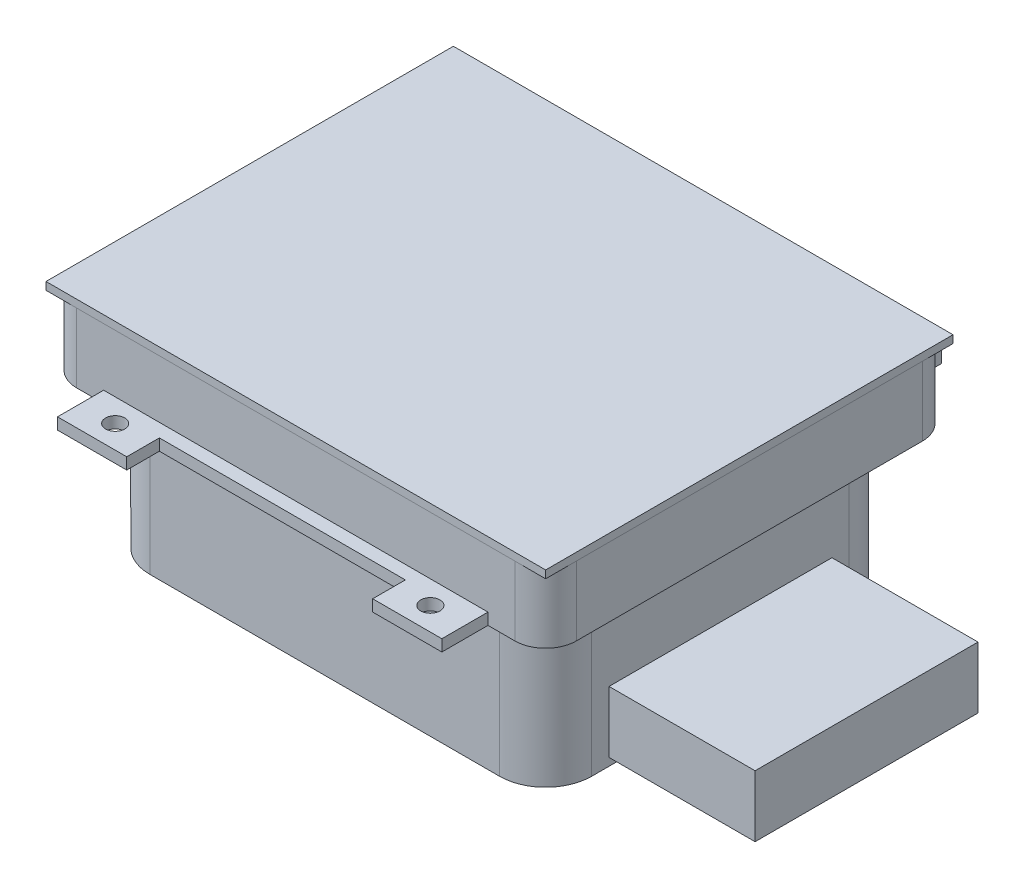
SolidWorks part; units mm, degrees
ref_plane "前视基准面" through (0, 0, 0) normal (0, 0, 1) x (1, 0, 0)
ref_plane "上视基准面" through (0, 0, 0) normal (0, 1, 0) x (1, 0, 0)
ref_plane "右视基准面" through (0, 0, 0) normal (1, 0, 0) x (0, 0, -1)
other "Configuration Table"
sketch "草图1" plane through (0, 0, 0) normal (0, 1, 0) x (1, 0, 0)
  line L1 (-32.5, 53) -> (32.5, 53)
  line L2 (-32.5, 53) -> (-32.5, 0)
  line L3 (-32.5, 0) -> (32.5, 0)
  line L4 (32.5, 53) -> (32.5, 0)
  point P4 (0, 0)
  dimension "D1" = 65
  dimension "D2" = 53
extrude "凸台-拉伸1" add sketch "草图1" against normal blind 9
sketch "草图3" plane through (0, -9, 0) normal (0, -1, 0) x (1, 0, 0)
  line L0 (0, 0) -> (0, -53) construction
  line L1 (32.5, -53) -> (-32.5, -53) construction
  line L2 (-32.5, -26.5) -> (32.5, -26.5) construction
  line L3 (-32.5, -53) -> (-32.5, 0) construction
  line L4 (32.5, 0) -> (32.5, -53) construction
  line L5 (-25, 0) -> (-25, 6)
  line L6 (-32.5, 0) -> (32.5, 0) construction
  line L7 (-25, 6) -> (-16, 6)
  line L8 (-16, 6) -> (-16, 1.75)
  line L9 (-16, 1.75) -> (16, 1.75)
  line L10 (0, 1.75) -> (0, 0)
  line L11 (25, 0) -> (-25, 0)
  line L12 (-32.5, 0) -> (32.5, 0) construction
  line L13 (16, 6) -> (16, 1.75)
  line L14 (25, 6) -> (16, 6)
  line L15 (25, 0) -> (25, 6)
  line L16 (25, -53) -> (25, -59)
  line L17 (16, -59) -> (16, -54.75)
  line L18 (25, -59) -> (16, -59)
  line L19 (-25, -53) -> (-25, -59)
  line L20 (-25, -59) -> (-16, -59)
  line L21 (-16, -59) -> (-16, -54.75)
  line L22 (-16, -54.75) -> (16, -54.75)
  line L23 (25, -53) -> (-25, -53)
  circle A0 centre (-20.5, 3) radius 1.25
  circle A1 centre (20.5, 3) radius 1.25
  circle A2 centre (-20.5, -56) radius 1.25
  circle A3 centre (20.5, -56) radius 1.25
  point P25 (-20.5, 6)
  line M2 (-32.5, -53) -> (32.5, -53)
  line M4 (32.5, 0) -> (-32.5, 0)
  dimension "D1" = 2.5
  dimension "D2" = 20.5
  dimension "D3" = 3
  dimension "D4" = 6
  dimension "D5" = 1.75
  dimension "D6" = 9
extrude "凸台-拉伸2" add sketch "草图3" against normal blind 1.5 contours L21 L22 L17 L18 L16 L19 L20 A3 A2 M2 | L10 L9 L8 L7 L5 A0 M4 | L15 L14 L13 L9 L10 A1 M4
ref_plane "基准面1" through (0, -29, 0) normal (0, -1, 0) x (-1, 0, 0)
sketch "草图4" plane through (0, -29, 0) normal (0, -1, 0) x (-1, 0, 0)
  line L0 (32.5, 26.5) -> (28.75, 26.5) construction
  line L1 (-28.75, 49.25) -> (28.75, 49.25)
  line L2 (-28.75, 49.25) -> (-28.75, 3.75)
  line L3 (-28.75, 3.75) -> (28.75, 3.75)
  line L4 (28.75, 49.25) -> (28.75, 3.75)
  line L5 (32.5, 53) -> (32.5, 0) construction
  point P4 (0, 3.75)
  dimension "D1" = 45.5
  dimension "D2" = 57.5
extrude "凸台-拉伸3" add sketch "草图4" against normal up to surface (20 mm away) up to face at (0, -9, -26.5)
chamfer "倒角1" distance 2 angle 45 4 edges at (28.75, -9, -26.5) (0, -9, -49.25) (-28.75, -9, -26.5) (0, -9, -3.75)
sketch "草图5" plane through (0, 0, 0) normal (0, 1, 0) x (1, 0, 0)
  line L0 (32.5, 26.5) -> (26.5, 26.5) construction
  line L1 (-26.5, 47) -> (26.5, 47)
  line L2 (-26.5, 47) -> (-26.5, 6)
  line L3 (-26.5, 6) -> (26.5, 6)
  line L4 (26.5, 47) -> (26.5, 6)
  line L5 (32.5, 0) -> (32.5, 53) construction
  line L6 (-32.5, 0) -> (32.5, 0) construction
  point P4 (0, 6)
  dimension "D1" = 6
  dimension "D2" = 6
extrude "切除-拉伸1" cut sketch "草图5" against normal blind 6 draft 60
sketch "草图6" plane through (0, 0, 0) normal (0, 1, 0) x (1, 0, 0)
  line L4 (-32.5, 53) -> (-32.5, 0)
  line L5 (-32.5, 0) -> (32.5, 0)
  line L6 (32.5, 0) -> (32.5, 53)
  line L7 (32.5, 53) -> (-32.5, 53)
  line L8 (-32.5, 53) -> (-32.5, 0)
  line L9 (-32.5, 0) -> (32.5, 0)
  line L10 (32.5, 0) -> (32.5, 53)
  line L11 (32.5, 53) -> (-32.5, 53)
  dimension "D1" = 0
extrude "凸台-拉伸4" add sketch "草图6" along normal blind 1 separate body
sketch "草图7" plane through (0, -6, 0) normal (0, 1, 0) x (1, 0, 0)
  line L0 (16.1077, 16.3923) -> (16.1077, 36.6077) construction
  circle A0 centre (0, 26.5) radius 3.2338
  point P4 (16.1077, 26.5)
extrude "切除-拉伸2" cut sketch "草图7" against normal blind 1 draft 60
sketch "草图8" plane through (28.75, 0, 0) normal (1, 0, 0) x (0, 0, -1)
  line L0 (26.5, 0) -> (26.5, -9) construction
  line L1 (12, -20) -> (41, -20)
  line L2 (12, -20) -> (12, -28)
  line L3 (12, -28) -> (41, -28)
  line L4 (41, -20) -> (41, -28)
  line L5 (0, 0) -> (53, 0) construction
  line L6 (1.75, -9) -> (51.25, -9) construction
  line L7 (-35.75, -29) -> (35.75, -29) construction
  point P10 (26.5, -20)
  dimension "D1" = 1
  dimension "D2" = 8
  dimension "D3" = 29
extrude "凸台-拉伸5" add sketch "草图8" along normal blind 19
fillet "圆角1" radius 4 4 edges at (32.5, -4.5, 0) (-32.5, -4.5, 0) (-32.5, -4.5, -53) (32.5, -4.5, -53)
fillet "圆角2" radius 6 4 edges at (-28.75, -20, -49.25) (28.75, -20, -49.25) (28.75, -20, -3.75) (-28.75, -20, -3.75)
